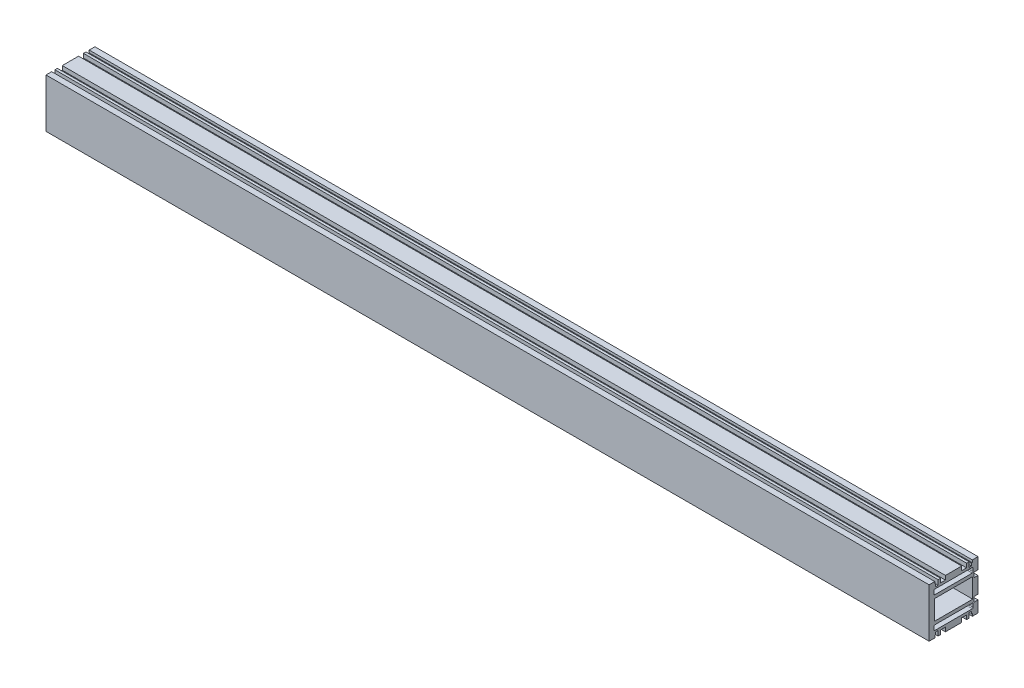
SolidWorks part; units mm, degrees
ref_plane "前视基准面" through (0, 0, 0) normal (0, 0, 1) x (1, 0, 0)
ref_plane "上视基准面" through (0, 0, 0) normal (0, 1, 0) x (1, 0, 0)
ref_plane "右视基准面" through (0, 0, 0) normal (1, 0, 0) x (0, 0, -1)
sketch "草图1" plane through (0, 0, 0) normal (1, 0, 0) x (0, 0, -1)
  line L0 (-15, 15) -> (15, -15) construction
  line L1 (-15, 15) -> (-11.5, 15)
  line L2 (-15, 15) -> (-15, -15)
  line L3 (-15, -15) -> (-11.5, -15)
  line L4 (15, 15) -> (15, 8)
  line L5 (15, 15) -> (-15, -15) construction
  line L6 (-11.5, 15) -> (-11.5, 13.5)
  line L7 (-11.5, 13.5) -> (-11, 13.5)
  line L8 (-11, 13.5) -> (-11, 12)
  line L9 (-11, 12) -> (-9.5, 12)
  line L10 (-9.5, 12) -> (-9.5, 15)
  line L11 (-9.5, 15) -> (-8, 15)
  line L12 (-8, 15) -> (-8, 12.5)
  line L13 (-8, 12.5) -> (-5, 12.5)
  line L14 (-5, 12.5) -> (-5, 15)
  line L15 (-5, 15) -> (5, 15)
  line L16 (0, 21.5201) -> (0, -18.309) construction
  line L17 (0, 55) -> (0, -55) construction
  line L18 (5, 12.5) -> (5, 15)
  line L19 (8, 12.5) -> (5, 12.5)
  line L20 (8, 15) -> (8, 12.5)
  line L21 (9.5, 15) -> (8, 15)
  line L22 (9.5, 12) -> (9.5, 15)
  line L23 (11, 12) -> (9.5, 12)
  line L24 (11, 13.5) -> (11, 12)
  line L25 (11.5, 13.5) -> (11, 13.5)
  line L26 (11.5, 15) -> (11.5, 13.5)
  line L27 (8, 15) -> (9.5, 15)
  line L28 (11.5, 15) -> (15, 15)
  line L29 (-19.8303, 0) -> (22.13, 0) construction
  line L30 (55, 0) -> (-55, 0) construction
  line L31 (8, -15) -> (9.5, -15)
  line L32 (11.5, -15) -> (11.5, -13.5)
  line L33 (11.5, -13.5) -> (11, -13.5)
  line L34 (11, -13.5) -> (11, -12)
  line L35 (11, -12) -> (9.5, -12)
  line L36 (9.5, -12) -> (9.5, -15)
  line L37 (9.5, -15) -> (8, -15)
  line L38 (8, -15) -> (8, -12.5)
  line L39 (8, -12.5) -> (5, -12.5)
  line L40 (5, -12.5) -> (5, -15)
  line L41 (-5, -15) -> (5, -15)
  line L42 (-5, -12.5) -> (-5, -15)
  line L43 (-8, -12.5) -> (-5, -12.5)
  line L44 (-8, -15) -> (-8, -12.5)
  line L45 (-9.5, -15) -> (-8, -15)
  line L46 (-9.5, -12) -> (-9.5, -15)
  line L47 (-11, -12) -> (-9.5, -12)
  line L48 (-11, -13.5) -> (-11, -12)
  line L49 (-11.5, -13.5) -> (-11, -13.5)
  line L50 (-11.5, -15) -> (-11.5, -13.5)
  line L51 (-9.5, -15) -> (-8, -15)
  line L52 (-5, -15) -> (5, -15)
  line L53 (8, -15) -> (9.5, -15)
  line L54 (11.5, -15) -> (15, -15)
  line L55 (15, 8) -> (12.5, 8)
  line L56 (12.5, 8) -> (12.5, 5)
  line L57 (12.5, 5) -> (15, 5)
  line L58 (12.5, -5) -> (15, -5)
  line L59 (12.5, -8) -> (12.5, -5)
  line L60 (15, -8) -> (12.5, -8)
  line L61 (15, 5) -> (15, -5)
  line L62 (15, -8) -> (15, -15)
  line L63 (12, -10.5) -> (12, -8.5)
  line L64 (-11.5, 11) -> (11.5, 11)
  line L65 (-12, 10.5) -> (-12, 8.5)
  line L66 (-11.5, 8) -> (11.5, 8)
  line L67 (12, 10.5) -> (12, 8.5)
  line L68 (-11.5, -8) -> (11.5, -8)
  line L69 (-12, -10.5) -> (-12, -8.5)
  line L70 (-11.5, -11) -> (11.5, -11)
  line L72 (-11.75, 6) -> (11.75, 6)
  line L73 (-11.75, 6) -> (-11.75, -6)
  line L74 (-11.75, -6) -> (11.75, -6)
  line L75 (11.75, 6) -> (11.75, -6)
  arc A0 (12, 8.5) -> (11.5, 8) centre (11.5, 8.5) cw
  arc A1 (11.5, 11) -> (12, 10.5) centre (11.5, 10.5) cw
  arc A2 (-11.5, 11) -> (-12, 10.5) centre (-11.5, 10.5) ccw
  arc A3 (-11.5, 8) -> (-12, 8.5) centre (-11.5, 8.5) cw
  arc A8 (-11.5, -8) -> (-12, -8.5) centre (-11.5, -8.5) ccw
  arc A9 (-11.5, -11) -> (-12, -10.5) centre (-11.5, -10.5) cw
  arc A10 (11.5, -11) -> (12, -10.5) centre (11.5, -10.5) ccw
  arc A11 (12, -8.5) -> (11.5, -8) centre (11.5, -8.5) ccw
  point P69 (12, 11)
  point P72 (-12, 11)
  point P77 (-11, -13.5)
  point P80 (11, -13.5)
  point P83 (11, 13.5)
  point P86 (-11, 13.5)
  point P99 (-12, -11)
  point P100 (12, -11)
  dimension "D17" = 0.5
  dimension "D1" = 3.5
  dimension "D2" = 1.5
  dimension "D3" = 0.5
  dimension "D4" = 1.5
  dimension "D5" = 3
  dimension "D6" = 30
  dimension "D7" = 30
  dimension "D8" = 1.5
  dimension "D9" = 2.5
  dimension "D10" = 3
  dimension "D11" = 2.5
  dimension "D12" = 7
  dimension "D13" = 3
  dimension "D14" = 4
  dimension "D15" = 3
  dimension "D16" = 24
  dimension "D19" = 23.5
  dimension "D20" = 12
extrude "凸台-拉伸1" add sketch "草图1" along normal mid plane 542
hole_wizard "M6 螺纹孔1" positions "草图3" profile "草图2" tap size "M6" standard "GB"
sketch "草图3" plane through (0, -15, 0) normal (0, -1, 0) x (-1, 0, 0)
  point P0 (251, 0)
  point P3 (236, 0)
  point P6 (-236, 0)
  point P9 (-251, 0)
sketch "草图2" plane through (-251, -15, 0) normal (1, 0, 0) x (0, 0, -1)
  line L0 (0, 0) -> (0, 20.5022)
  line L1 (0, 20.5022) -> (2.5, 19)
  line L2 (2.5, 19) -> (2.5, 0)
  line L5 (2.5, 0) -> (0, 0)
  line L10 (0, 20.5022) -> (-2.5, 19) construction
  line L11 (0, -6.35) -> (0, 107.95) construction
  dimension "螺纹孔钻头直径" = 5
  dimension "螺纹孔钻头深度" = 19
  dimension "导头角度" = 118
cosmetic thread "孔螺蚊线1" parameters "D1"=9, "D2"=6
cosmetic thread "孔螺蚊线2" parameters "D1"=9, "D2"=6
cosmetic thread "孔螺蚊线3" parameters "D1"=9, "D2"=6
cosmetic thread "孔螺蚊线4" parameters "D1"=9, "D2"=6
hole_wizard "M6 螺纹孔2" positions "草图5" profile "草图4" tap size "M6" standard "GB"
sketch "草图5" plane through (0, 0, -15) normal (0, 0, -1) x (-1, 0, 0)
  point P0 (-236, 0)
  point P3 (-251, 0)
sketch "草图4" plane through (236, 0, -15) normal (1, 0, 0) x (0, 1, 0)
  line L0 (0, 0) -> (0, 20.5022)
  line L1 (0, 20.5022) -> (2.5, 19)
  line L2 (2.5, 19) -> (2.5, 0)
  line L5 (2.5, 0) -> (0, 0)
  line L10 (0, 20.5022) -> (-2.5, 19) construction
  line L11 (0, -6.35) -> (0, 107.95) construction
  dimension "螺纹孔钻头直径" = 5
  dimension "螺纹孔钻头深度" = 19
  dimension "导头角度" = 118
cosmetic thread "孔螺蚊线5" parameters "D1"=3.25, "D2"=6
cosmetic thread "孔螺蚊线6" parameters "D1"=3.25, "D2"=6
hole_wizard "M4 螺纹孔1" positions "草图8" profile "草图6" tap size "M4" standard "GB"
sketch "草图8" plane through (0, 0, -15) normal (0, 0, -1) x (-1, 0, 0)
  line L0 (-271, 15) -> (271, 15) construction
  line L1 (271, 5) -> (271, -5) construction
  line L3 (-271, 5) -> (-271, -5) construction
  point P0 (-201, 0)
  point P2 (21.5, 0)
  point P4 (60.5, 0)
  point P6 (258, 0)
  dimension "D1" = 15
  dimension "D2" = 13
  dimension "D3" = 210.5
  dimension "D4" = 15
  dimension "D5" = 15
  dimension "D6" = 249.5
  dimension "D7" = 15
  dimension "D8" = 70
sketch "草图6" plane through (201, 0, -15) normal (1, 0, 0) x (0, 1, 0)
  line L0 (0, 0) -> (0, 15.9914)
  line L1 (0, 15.9914) -> (1.65, 15)
  line L2 (1.65, 15) -> (1.65, 0)
  line L5 (1.65, 0) -> (0, 0)
  line L10 (0, 15.9914) -> (-1.65, 15) construction
  line L11 (0, -6.35) -> (0, 107.95) construction
  dimension "螺纹孔钻头直径" = 3.3
  dimension "螺纹孔钻头深度" = 15
  dimension "导头角度" = 118
cosmetic thread "孔螺蚊线7" parameters "D1"=3.25, "D2"=4
cosmetic thread "孔螺蚊线8" parameters "D1"=3.25, "D2"=4
cosmetic thread "孔螺蚊线9" parameters "D1"=3.25, "D2"=4
cosmetic thread "孔螺蚊线10" parameters "D1"=3.25, "D2"=4
